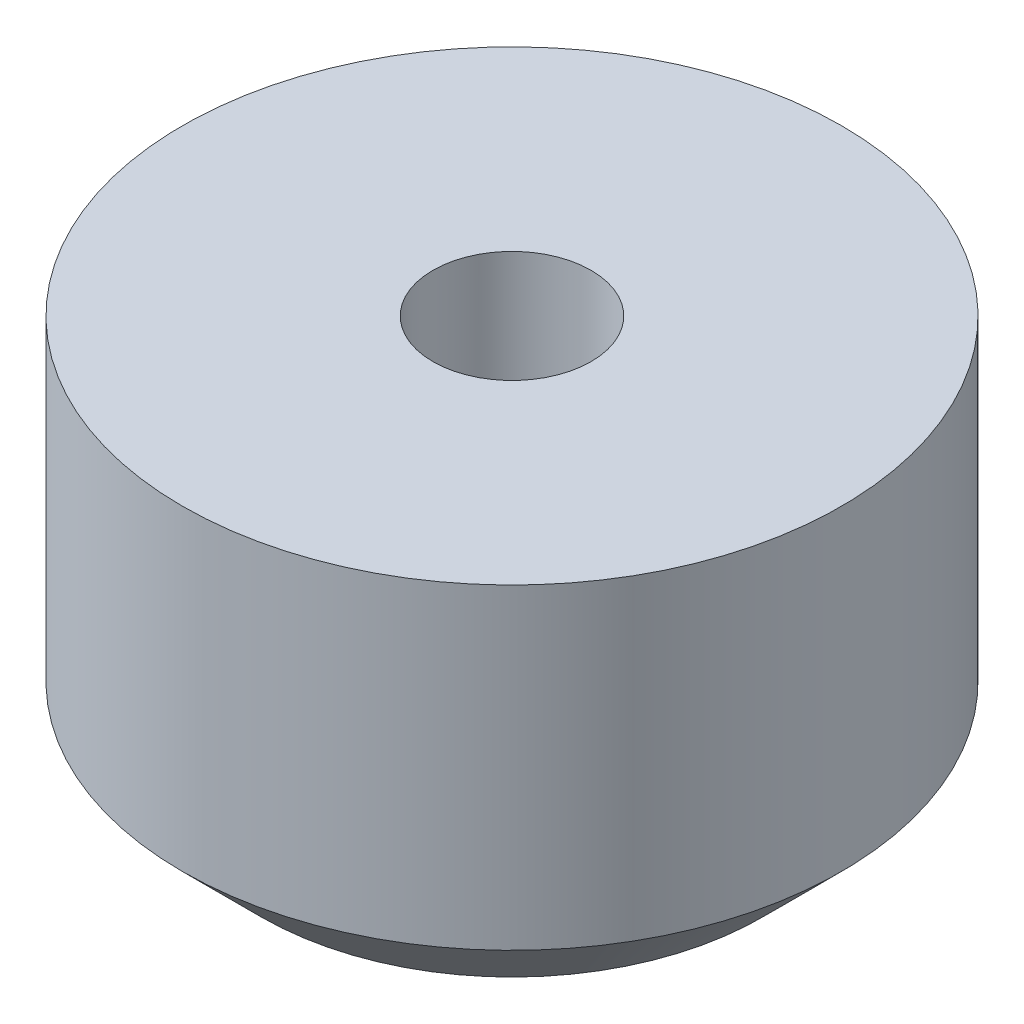
SolidWorks part; units mm, degrees
material "Rubber"
ref_plane "Front Plane" through (0, 0, 0) normal (0, 0, 1) x (1, 0, 0)
ref_plane "Top Plane" through (0, 0, 0) normal (0, 1, 0) x (1, 0, 0)
ref_plane "Right Plane" through (0, 0, 0) normal (1, 0, 0) x (0, 0, -1)
sketch "Sketch1" plane through (0, 0, 0) normal (0, 1, 0) x (1, 0, 0)
  circle A0 centre (0, 0) radius 12.5
  circle A1 centre (0, 0) radius 3
  dimension "D1" = 6
  dimension "D2" = 25
extrude "Boss-Extrude1" add sketch "Sketch1" along normal blind 15
chamfer "Chamfer1" distance 3 angle 45 1 edges at (0, 0, 12.5)
sketch "Sketch2" plane through (0, 0, 0) normal (0, -1, 0) x (1, 0, 0)
  circle A0 centre (0, 0) radius 6
  dimension "D1" = 12
extrude "Cut-Extrude1" cut sketch "Sketch2" against normal blind 7
